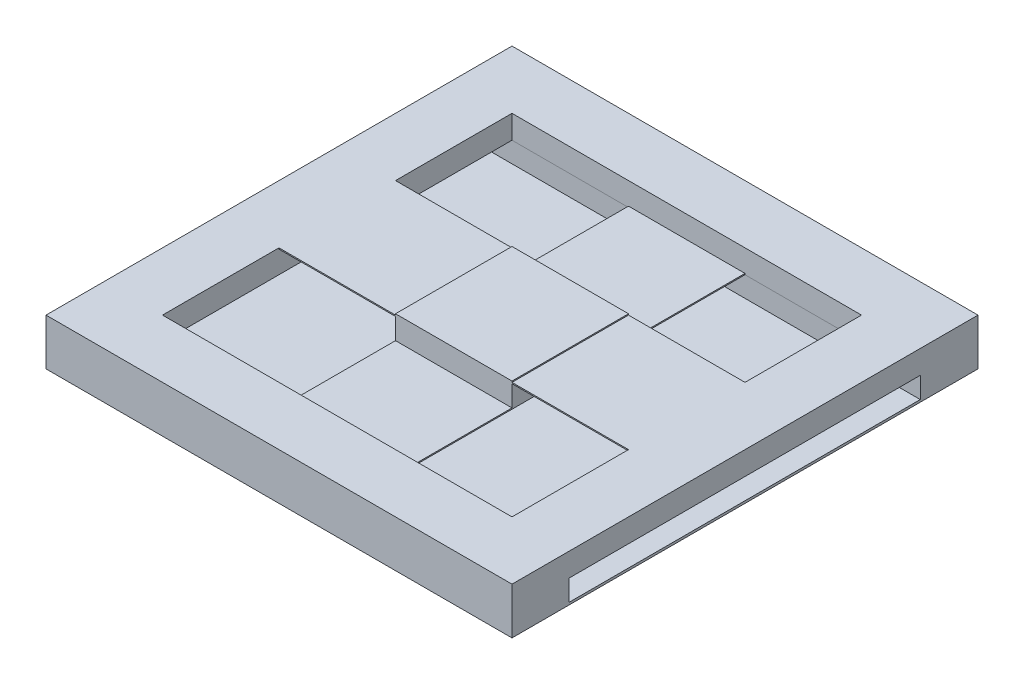
SolidWorks part; units mm, degrees
ref_plane "Front Plane" through (0, 0, 0) normal (0, 0, 1) x (1, 0, 0)
ref_plane "Top Plane" through (0, 0, 0) normal (0, 1, 0) x (1, 0, 0)
ref_plane "Right Plane" through (0, 0, 0) normal (1, 0, 0) x (0, 0, -1)
sketch "Sketch1" plane through (0, 0, 0) normal (0, 1, 0) x (1, 0, 0)
  line L1 (-0.5, -0.5) -> (0.5, -0.5)
  line L2 (-0.5, -0.5) -> (-0.5, 0.5)
  line L3 (-0.5, 0.5) -> (0.5, 0.5)
  line L4 (0.5, -0.5) -> (0.5, 0.5)
  line L5 (-0.5, -0.5) -> (0.5, 0.5) construction
  line L6 (-0.5, 0.5) -> (0.5, -0.5) construction
  point P0 (0, 0)
  dimension "D1" = 1
  dimension "D2" = 1
extrude "Boss-Extrude1" add sketch "Sketch1" along normal blind 0.2
sketch "Sketch2" plane through (0, 0.2, 0) normal (0, 1, 0) x (1, 0, 0)
  line L0 (-2, -2) -> (-2, 2)
  line L1 (-1.5, -1.5) -> (1.5, -1.5)
  line L2 (-1.5, -1.5) -> (-1.5, 1.5)
  line L3 (-1.5, 1.5) -> (1.5, 1.5)
  line L4 (1.5, -1.5) -> (1.5, 1.5)
  line L5 (-1.5, -1.5) -> (1.5, 1.5) construction
  line L6 (-1.5, 1.5) -> (1.5, -1.5) construction
  line L7 (-2, 2) -> (2, 2)
  line L8 (2, -2) -> (2, 2)
  line L9 (-2, -2) -> (2, -2)
  point P0 (0, 0)
  dimension "D1" = 3
  dimension "D2" = 3
  dimension "D3" = 0.5
extrude "Boss-Extrude2" add sketch "Sketch2" against normal up to surface (0.2 mm away) separate body contours L2 L3 L4 L1 | L0 L7 L8 L9 up to face at (0, 0, 0)
sketch "Sketch3" plane through (0, 0, 0) normal (0, -1, 0) x (1, 0, 0)
  line L0 (-1.5, -1.5) -> (1.5, -1.5) construction
  line L1 (-0.5, -0.5) -> (0.5, -0.5)
  line L2 (-0.5, -0.5) -> (-0.5, -1.5)
  line L3 (-0.5, -1.5) -> (0.5, -1.5)
  line L4 (0.5, -0.5) -> (0.5, -1.5)
  dimension "D1" = 1
extrude "Boss-Extrude3" add sketch "Sketch3" against normal blind 0.01
ref_plane "Plane1" through (0, 0, 0) normal (0, 0, 1) x (1, 0, 0)
mirror "Mirror1" about plane through (0, 0, 0) normal (0, 0, 1) of "Boss-Extrude3"
sketch "Sketch4" plane through (0, 0.2, 0) normal (0, 1, 0) x (1, 0, 0)
  line L0 (1.5, -1.5) -> (1.5, 1.5) construction
  line L1 (0.5, 0.5) -> (1.5, 0.5)
  line L2 (0.5, 0.5) -> (0.5, -0.5)
  line L3 (0.5, -0.5) -> (1.5, -0.5)
  line L4 (1.5, 0.5) -> (1.5, -0.5)
  dimension "D1" = 1
extrude "Boss-Extrude4" add sketch "Sketch4" against normal blind 0.01
ref_plane "Plane3" through (0, 0, 0) normal (1, 0, 0) x (0, 0, -1)
mirror "Mirror2" about plane through (0, 0, 0) normal (1, 0, 0) of "Boss-Extrude4"
sketch "Sketch6" plane through (0, 0.2, 0) normal (0, 1, 0) x (1, 0, 0)
  line L0 (0.5, 0.5) -> (-0.5, 0.5) construction
  line L1 (-0.5, -0.5) -> (0.5, -0.5)
  line L2 (-0.5, -0.5) -> (-0.5, 0.5)
  line L3 (-0.5, 0.5) -> (0.5, 0.5)
  line L4 (0.5, -0.5) -> (0.5, 0.5)
  line L5 (-0.5, -0.5) -> (0.5, 0.5) construction
  line L6 (-0.5, 0.5) -> (0.5, -0.5) construction
  line L7 (1.5, 0.5) -> (-1.5, 0.5) construction
  point P0 (0, 0)
extrude "Boss-Extrude5" add sketch "Sketch6" along normal blind 0.01
sketch "Sketch8" plane through (0, 0, 0) normal (0, -1, 0) x (1, 0, 0)
  line L0 (-2, 2) -> (-2, -2) construction
  line L1 (2, 2) -> (-2, 2)
  line L2 (2, 2) -> (2, 1.5098)
  line L3 (2, 1.5098) -> (-2, 1.5098)
  line L4 (-2, 2) -> (-2, 1.5098)
  line L5 (2, -2) -> (-2, -2)
  line L6 (2, -2) -> (2, -1.5044)
  line L7 (2, -1.5044) -> (-2, -1.5044)
  line L8 (-2, -2) -> (-2, -1.5044)
extrude "Boss-Extrude6" add sketch "Sketch8" along normal blind 0.2
sketch "Sketch9" plane through (0, 0, 1.5098) normal (0, 0, -1) x (-1, 0, 0)
  line L0 (2, -0.2) -> (2, 0.2) construction
  line L1 (-2, -0.2) -> (2, -0.2)
  line L2 (-2, -0.2) -> (-2, -0.18)
  line L3 (-2, -0.18) -> (2, -0.18)
  line L4 (2, -0.2) -> (2, -0.18)
  dimension "D1" = 0.02
extrude "Boss-Extrude7" add sketch "Sketch9" along normal up to surface (3.0142 mm away) up to face at (0, -0.1, -1.5044)
